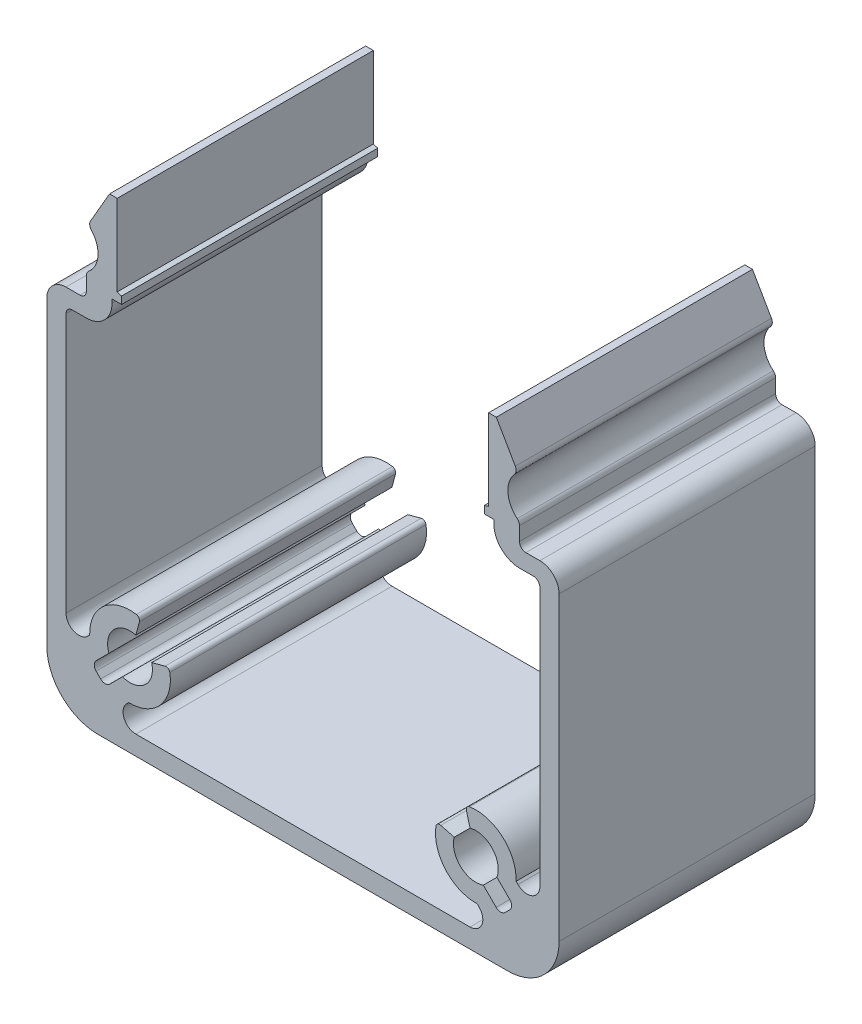
SolidWorks part; units mm, degrees
ref_plane "Front Plane" through (0, 0, 0) normal (0, 0, 1) x (1, 0, 0)
ref_plane "Top Plane" through (0, 0, 0) normal (0, 1, 0) x (1, 0, 0)
ref_plane "Right Plane" through (0, 0, 0) normal (1, 0, 0) x (0, 0, -1)
ref_plane "Plane1" through (0, 0, 20) normal (0, 0, 1) x (1, 0, 0)
sketch "Sketch1" plane through (0, 0, 20) normal (0, 0, 1) x (1, 0, 0)
  line L0 (4, 0) -> (36, 0)
  line L1 (40, 4) -> (40, 27.5)
  line L2 (38.5, 29) -> (37.4085, 29)
  line L3 (36.9085, 29.5) -> (36.9085, 30.572)
  line L4 (36.583, 34.4315) -> (35.1, 37)
  line L5 (35.1, 37) -> (34.5, 37)
  line L6 (34.5, 37) -> (34.5, 30.6727)
  line L7 (34.5, 30.6727) -> (34.1585, 30.5611)
  line L8 (34.1585, 30.5611) -> (34.1585, 29.9899)
  line L9 (34.1585, 29.9899) -> (34.9085, 29.9899)
  line L10 (34.9085, 29.9899) -> (34.9085, 29.7)
  line L11 (36.9085, 27.7) -> (38, 27.7)
  line L12 (38.5, 27.2) -> (38.5, 6.9548)
  line L13 (36.7929, 6.2477) -> (36.6482, 6.3924)
  line L14 (32.7665, 9.2376) -> (33.0471, 8.1904)
  line L15 (35.1484, 5.9123) -> (36.1464, 4.9142)
  line L16 (36.1464, 4.2071) -> (35.7929, 3.8536)
  line L17 (35.0858, 3.8536) -> (34.0877, 4.8516)
  line L18 (31.8096, 6.9529) -> (30.7624, 7.2335)
  line L19 (33.6076, 3.3518) -> (33.7523, 3.2071)
  line L20 (33.0452, 1.5) -> (6.9548, 1.5)
  line L21 (6.2477, 3.2071) -> (6.3924, 3.3518)
  line L22 (9.2376, 7.2335) -> (8.1904, 6.9529)
  line L23 (5.9123, 4.8516) -> (4.9142, 3.8536)
  line L24 (4.2071, 3.8536) -> (3.8536, 4.2071)
  line L25 (3.8536, 4.9142) -> (4.8516, 5.9123)
  line L26 (6.9529, 8.1904) -> (7.2335, 9.2376)
  line L27 (3.3518, 6.3924) -> (3.2071, 6.2477)
  line L28 (1.5, 6.9548) -> (1.5, 27.2)
  line L29 (2, 27.7) -> (3.0915, 27.7)
  line L30 (5.0915, 29.7) -> (5.0915, 29.9899)
  line L31 (5.0915, 29.9899) -> (5.8415, 29.9899)
  line L32 (5.8415, 29.9899) -> (5.8415, 30.5611)
  line L33 (5.8415, 30.5611) -> (5.5, 30.6727)
  line L34 (5.5, 30.6727) -> (5.5, 37)
  line L35 (5.5, 37) -> (4.9, 37)
  line L36 (4.9, 37) -> (3.417, 34.4315)
  line L37 (3.0915, 30.572) -> (3.0915, 29.5)
  line L38 (2.5915, 29) -> (1.5, 29)
  line L39 (0, 27.5) -> (0, 4)
  arc A0 (36, 0) -> (40, 4) centre (36, 4) ccw
  arc A1 (40, 27.5) -> (38.5, 29) centre (38.5, 27.5) ccw
  arc A2 (37.4085, 29) -> (36.9085, 29.5) centre (37.4085, 29.5) cw
  arc A3 (36.9085, 30.572) -> (36.7268, 30.9576) centre (36.4085, 30.572) ccw
  arc A4 (36.7268, 30.9576) -> (36.52, 33.8452) centre (38, 32.5) cw
  arc A5 (36.52, 33.8452) -> (36.583, 34.4315) centre (36.1499, 34.1815) ccw
  arc A6 (34.9085, 29.7) -> (36.9085, 27.7) centre (36.9085, 29.7) ccw
  arc A7 (38, 27.7) -> (38.5, 27.2) centre (38, 27.2) cw
  arc A8 (38.5, 6.9548) -> (36.7929, 6.2477) centre (37.5, 6.9548) cw
  arc A9 (36.6482, 6.3924) -> (33.0095, 9.6116) centre (33.5, 6.5) ccw
  arc A10 (33.0095, 9.6116) -> (32.7665, 9.2376) centre (33.0562, 9.3152) ccw
  arc A11 (33.0471, 8.1904) -> (35.1484, 5.9123) centre (33.5, 6.5) cw
  arc A12 (36.1464, 4.9142) -> (36.1464, 4.2071) centre (35.7929, 4.5607) cw
  arc A13 (35.7929, 3.8536) -> (35.0858, 3.8536) centre (35.4393, 4.2071) cw
  arc A14 (34.0877, 4.8516) -> (31.8096, 6.9529) centre (33.5, 6.5) cw
  arc A15 (30.7624, 7.2335) -> (30.3884, 6.9905) centre (30.6848, 6.9438) ccw
  arc A16 (30.3884, 6.9905) -> (33.6076, 3.3518) centre (33.5, 6.5) ccw
  arc A17 (33.7523, 3.2071) -> (33.0452, 1.5) centre (33.0452, 2.5) cw
  arc A18 (6.9548, 1.5) -> (6.2477, 3.2071) centre (6.9548, 2.5) cw
  arc A19 (6.3924, 3.3518) -> (9.6116, 6.9905) centre (6.5, 6.5) ccw
  arc A20 (9.6116, 6.9905) -> (9.2376, 7.2335) centre (9.3152, 6.9438) ccw
  arc A21 (8.1904, 6.9529) -> (5.9123, 4.8516) centre (6.5, 6.5) cw
  arc A22 (4.9142, 3.8536) -> (4.2071, 3.8536) centre (4.5607, 4.2071) cw
  arc A23 (3.8536, 4.2071) -> (3.8536, 4.9142) centre (4.2071, 4.5607) cw
  arc A24 (4.8516, 5.9123) -> (6.9529, 8.1904) centre (6.5, 6.5) cw
  arc A25 (7.2335, 9.2376) -> (6.9905, 9.6116) centre (6.9438, 9.3152) ccw
  arc A26 (6.9905, 9.6116) -> (3.3518, 6.3924) centre (6.5, 6.5) ccw
  arc A27 (3.2071, 6.2477) -> (1.5, 6.9548) centre (2.5, 6.9548) cw
  arc A28 (1.5, 27.2) -> (2, 27.7) centre (2, 27.2) cw
  arc A29 (3.0915, 27.7) -> (5.0915, 29.7) centre (3.0915, 29.7) ccw
  arc A30 (3.417, 34.4315) -> (3.48, 33.8452) centre (3.8501, 34.1815) ccw
  arc A31 (3.48, 33.8452) -> (3.2732, 30.9576) centre (2, 32.5) cw
  arc A32 (3.2732, 30.9576) -> (3.0915, 30.572) centre (3.5915, 30.572) ccw
  arc A33 (3.0915, 29.5) -> (2.5915, 29) centre (2.5915, 29.5) cw
  arc A34 (1.5, 29) -> (0, 27.5) centre (1.5, 27.5) ccw
  arc A35 (0, 4) -> (4, 0) centre (4, 4) ccw
extrude "Boss-Extrude1" add sketch "Sketch1" against normal blind 20
